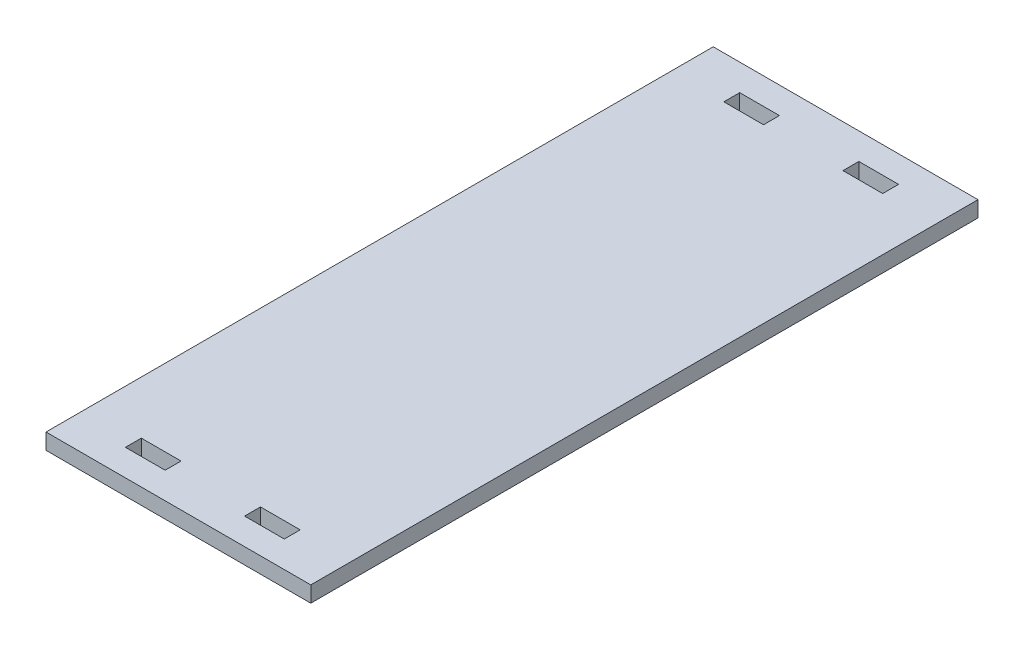
SolidWorks part; units mm, degrees
ref_plane "Front Plane" through (0, 0, 0) normal (0, 0, 1) x (1, 0, 0)
ref_plane "Top Plane" through (0, 0, 0) normal (0, 1, 0) x (1, 0, 0)
ref_plane "Right Plane" through (0, 0, 0) normal (1, 0, 0) x (0, 0, -1)
sketch "Sketch1" plane through (0, 0, 0) normal (0, 1, 0) x (1, 0, 0)
  line L0 (0, 0) -> (-100, 0)
  line L1 (-100, 0) -> (-100, -252)
  line L3 (-65, -10) -> (-65, -16)
  line L5 (-35, -16) -> (-35, -10)
  line L11 (-65, -236) -> (-65, -242)
  line L14 (-100, -252) -> (0, -252)
  line L17 (-35, -242) -> (-35, -236)
  line L18 (-65, -10) -> (-80, -10)
  line L20 (-80, -10) -> (-80, -16)
  line L22 (-80, -16) -> (-65, -16)
  line L23 (-35, -10) -> (-20, -10)
  line L25 (-20, -10) -> (-20, -16)
  line L27 (-20, -16) -> (-35, -16)
  line L28 (0, -252) -> (0, 0)
  line L29 (-65, -236) -> (-80, -236)
  line L31 (-80, -236) -> (-80, -242)
  line L33 (-80, -242) -> (-65, -242)
  line L34 (-35, -236) -> (-20, -236)
  line L36 (-20, -236) -> (-20, -242)
  line L38 (-20, -242) -> (-35, -242)
  dimension "D1" = 6
  dimension "D2" = 30
  dimension "D3" = 15
  dimension "D4" = 20
  dimension "D5" = 220
  dimension "D6" = 10
  dimension "D7" = 30
  dimension "D8" = 15
  dimension "D9" = 6
  dimension "D10" = 100
  dimension "D12" = 20
  dimension "D14" = 10
extrude "Boss-Extrude1" add sketch "Sketch1" along normal blind 6
